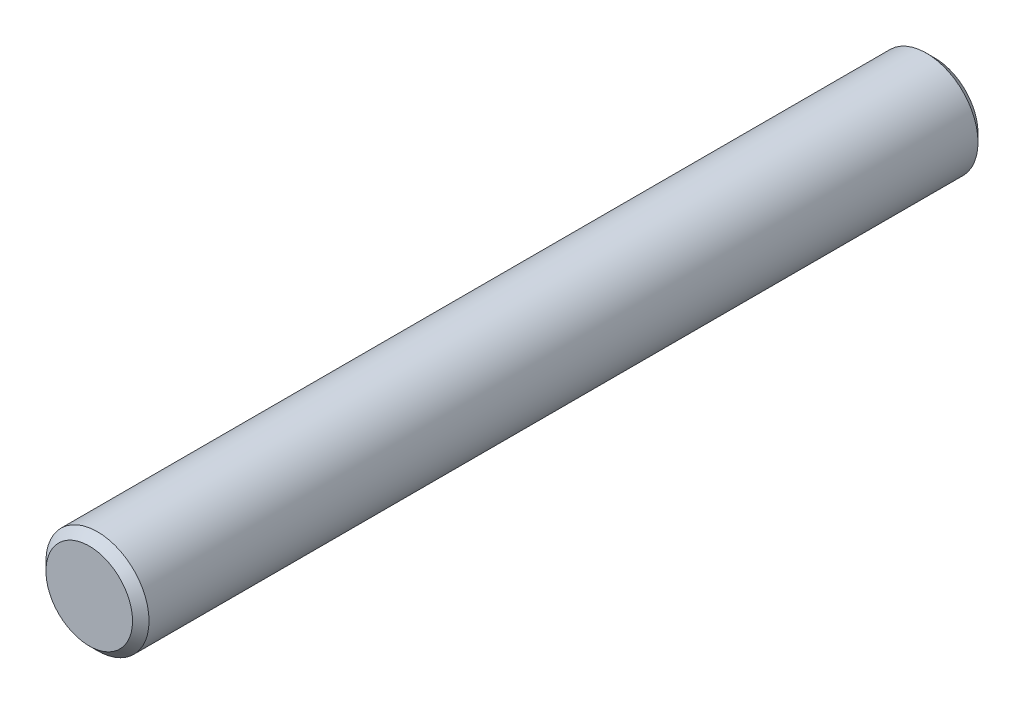
SolidWorks part; units mm, degrees
material "AISI 316 Stainless Steel Sheet (SS)"
ref_plane "Front Plane" through (0, 0, 0) normal (0, 0, 1) x (1, 0, 0)
ref_plane "Top Plane" through (0, 0, 0) normal (0, 1, 0) x (1, 0, 0)
ref_plane "Right Plane" through (0, 0, 0) normal (1, 0, 0) x (0, 0, -1)
sketch "Sketch1" plane through (0, 0, 0) normal (0, 0, 1) x (1, 0, 0)
  circle A0 centre (0, 0) radius 6.35
  dimension "D1" = 12.7
extrude "Boss-Extrude1" add sketch "Sketch1" along normal blind 104.14
chamfer "Chamfer1" distance 1.016 angle 45 2 edges at (6.35, 0, 0) (6.35, 0, 104.14)
